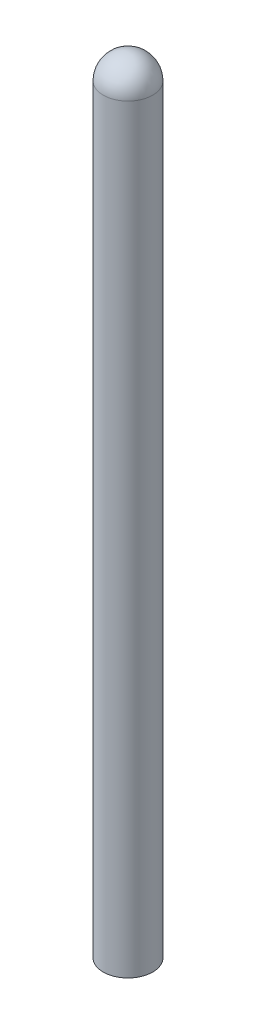
SolidWorks part; units mm, degrees
ref_plane "前视基准面" through (0, 0, 0) normal (0, 0, 1) x (1, 0, 0)
ref_plane "上视基准面" through (0, 0, 0) normal (0, 1, 0) x (1, 0, 0)
ref_plane "右视基准面" through (0, 0, 0) normal (1, 0, 0) x (0, 0, -1)
other "Configuration Table"
sketch "草图1" plane through (0, 0, 0) normal (0, 1, 0) x (1, 0, 0)
  circle A0 centre (0, 0) radius 0.75
  dimension "D1" = 1.5
extrude "凸台-拉伸1" add sketch "草图1" along normal blind 23
sketch "草图2" plane through (0, 0, 0) normal (1, 0, 0) x (0, 0, -1)
  line L0 (0.75, 23) -> (-0.75, 23) construction
  line L1 (0, 23.75) -> (0, 22.25)
  arc A0 (0, 22.25) -> (0, 23.75) centre (0, 23) ccw
revolve "旋转1" add sketch "草图2" angle 360 about L1
